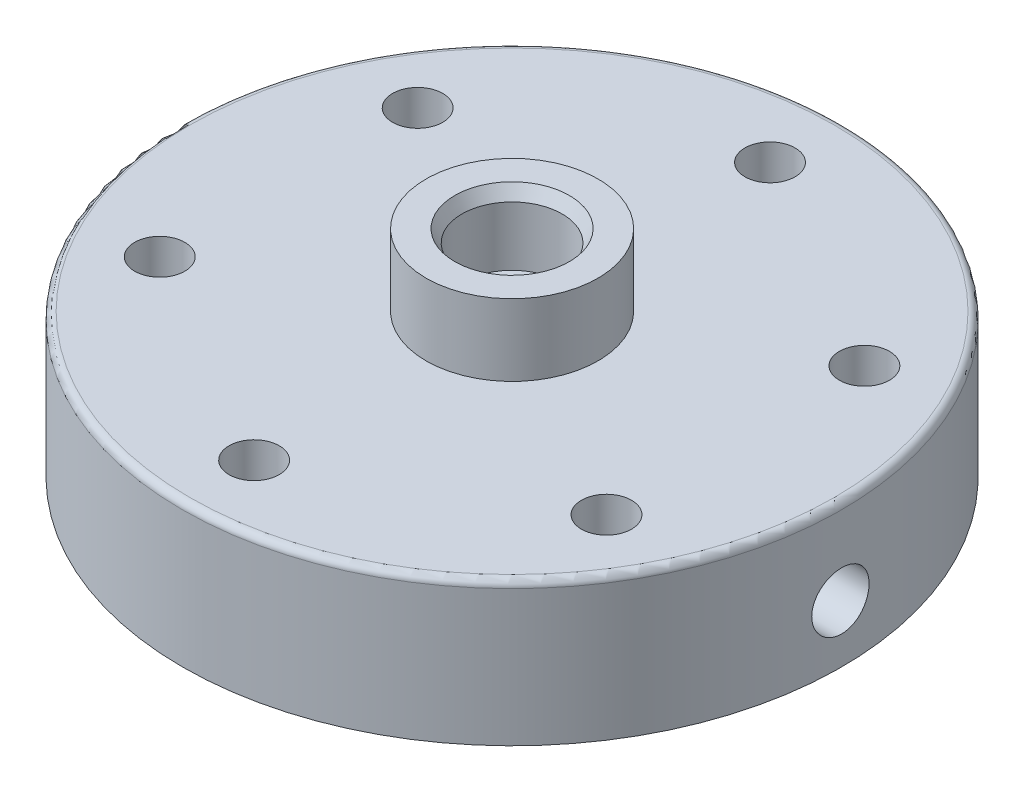
SolidWorks part; units mm, degrees
ref_plane "Front Plane" through (0, 0, 0) normal (0, 0, 1) x (1, 0, 0)
ref_plane "Top Plane" through (0, 0, 0) normal (0, 1, 0) x (1, 0, 0)
ref_plane "Right Plane" through (0, 0, 0) normal (1, 0, 0) x (0, 0, -1)
sketch "Sketch1" plane through (0, 0, 0) normal (0, 1, 0) x (1, 0, 0)
  circle A0 centre (0, 0) radius 46
  circle A1 centre (0, 0) radius 36 construction
  circle A2 centre (0, 36) radius 3.5
  circle A3 centre (31.1769, 18) radius 3.5
  circle A4 centre (31.1769, -18) radius 3.5
  circle A5 centre (0, -36) radius 3.5
  circle A6 centre (-31.1769, -18) radius 3.5
  circle A7 centre (-31.1769, 18) radius 3.5
  point P18 (0, 0)
  dimension "D1" = 92
  dimension "D2" = 72
  dimension "D3" = 7
  dimension "D4" = 6
extrude "Boss-Extrude1" add sketch "Sketch1" along normal blind 20
fillet "Fillet1" radius 1 1 edges at (0, 20, 46)
sketch "Sketch2" plane through (0, 20, 0) normal (0, 1, 0) x (1, 0, 0)
  circle A0 centre (0, 0) radius 12
  dimension "D1" = 24
extrude "Boss-Extrude2" add sketch "Sketch2" along normal blind 10
sketch "Sketch3" plane through (0, 0, 0) normal (0, -1, 0) x (1, 0, 0)
  circle A0 centre (0, 0) radius 33
  dimension "D1" = 66
extrude "Cut-Extrude1" cut sketch "Sketch3" against normal blind 14
sketch "Sketch4" plane through (0, 14, 0) normal (0, -1, 0) x (1, 0, 0)
  circle A0 centre (0, 0) radius 2.5
  dimension "D1" = 5
extrude "Cut-Extrude2" cut sketch "Sketch4" against normal blind 6
sketch "Sketch5" plane through (0, 30, 0) normal (0, 1, 0) x (1, 0, 0)
  circle A0 centre (0, 0) radius 7
  dimension "D1" = 14
extrude "Cut-Extrude3" cut sketch "Sketch5" against normal blind 10
cosmetic thread "Cosmetic Thread1" parameters "D1"=10, "D2"=16
chamfer "Chamfer1" distance 1 angle 60 1 edges at (0, 30, 7)
sketch "Sketch6" plane through (0, 0, 0) normal (1, 0, 0) x (0, 0, -1)
  circle A0 centre (0, 8) radius 4
  dimension "D1" = 8
  dimension "D2" = 8
extrude "Cut-Extrude4" cut sketch "Sketch6" along normal blind 80
